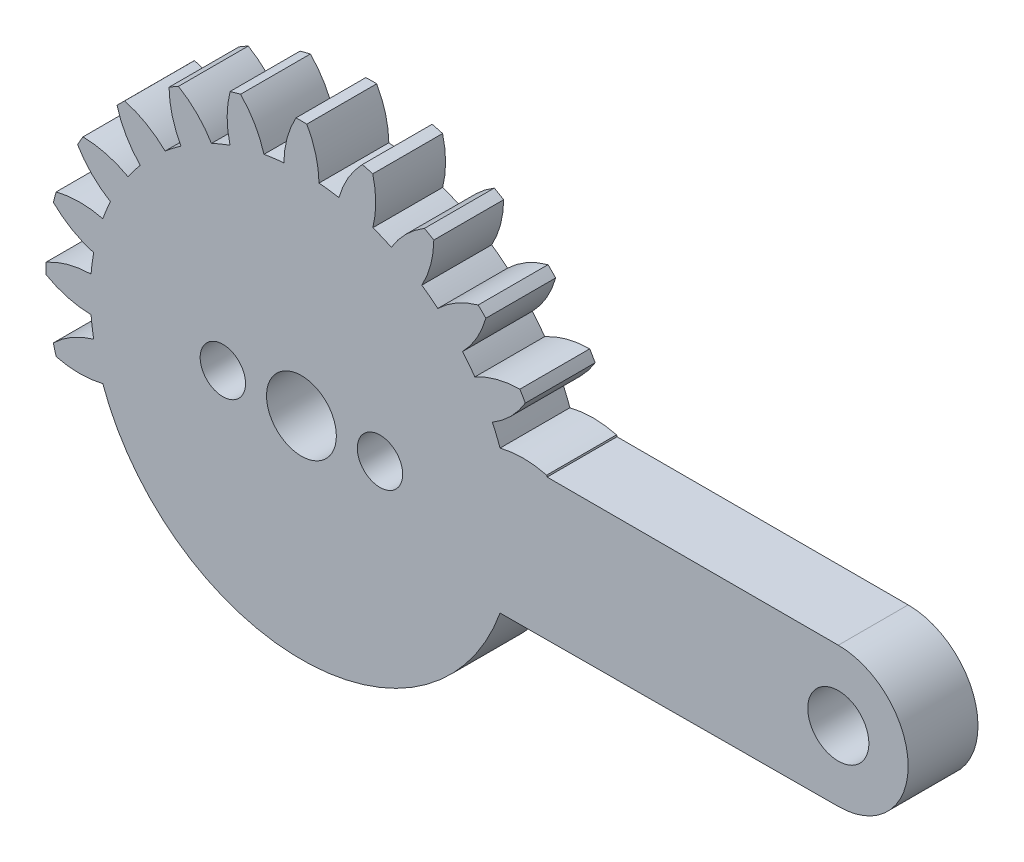
SolidWorks part; units mm, degrees
ref_plane "Front Plane" through (0, 0, 0) normal (0, 0, 1) x (1, 0, 0)
ref_plane "Top Plane" through (0, 0, 0) normal (0, 1, 0) x (1, 0, 0)
ref_plane "Right Plane" through (0, 0, 0) normal (1, 0, 0) x (0, 0, -1)
sketch "Sketch1" plane through (0, 0, 0) normal (0, 0, 1) x (1, 0, 0)
  line L0 (0, 0) -> (0, 14.63) construction
  line L1 (0, 0) -> (34.8406, 0) construction
  line L2 (11.4091, 4) -> (30.75, 4)
  line L3 (30.7686, -4) -> (11.3771, -4.0902)
  circle A0 centre (0, 0) radius 14.63
  circle A1 centre (0, 0) radius 12.09
  circle A2 centre (0, 0) radius 1.75
  arc A3 (0.31, 14.6267) -> (1.0062, 12.0481) centre (-4.3933, 11.9736) cw
  arc A4 (-0.31, 14.6267) -> (-1.0062, 12.0481) centre (4.3933, 11.9736) ccw
  arc A5 (4.0851, 14.0481) -> (4.0902, 11.3771) centre (-1.1446, 12.7027) cw
  arc A6 (3.4862, 14.2086) -> (2.1464, 11.898) centre (7.3426, 10.4285) ccw
  arc A7 (7.5818, 12.5121) -> (6.8954, 9.9308) centre (2.1821, 12.5661) cw
  arc A8 (7.0449, 12.8221) -> (5.1526, 10.937) centre (9.7915, 8.1728) ccw
  arc A9 (10.5619, 10.1234) -> (9.2308, 7.8078) centre (5.3601, 11.5731) cw
  arc A10 (10.1234, 10.5619) -> (7.8078, 9.2308) centre (11.5731, 5.3601) ccw
  arc A11 (12.8221, 7.0449) -> (10.937, 5.1526) centre (8.1728, 9.7915) cw
  arc A12 (12.5121, 7.5818) -> (9.9308, 6.8954) centre (12.5661, 2.1821) ccw
  arc A13 (14.2086, 3.4862) -> (11.898, 2.1464) centre (10.4285, 7.3426) cw
  arc A14 (14.0481, 4.0851) -> (11.3771, 4.0902) centre (12.7027, -1.1446) ccw
  arc A15 (14.6267, -0.31) -> (12.0481, -1.0062) centre (11.9736, 4.3933) cw
  arc A16 (14.6267, 0.31) -> (12.0481, 1.0062) centre (11.9736, -4.3933) ccw
  arc A17 (14.0481, -4.0851) -> (11.3771, -4.0902) centre (12.7027, 1.1446) cw
  arc A18 (14.2086, -3.4862) -> (11.898, -2.1464) centre (10.4285, -7.3426) ccw
  arc A19 (12.5121, -7.5818) -> (9.9308, -6.8954) centre (12.5661, -2.1821) cw
  arc A20 (12.8221, -7.0449) -> (10.937, -5.1526) centre (8.1728, -9.7915) ccw
  arc A21 (10.1234, -10.5619) -> (7.8078, -9.2308) centre (11.5731, -5.3601) cw
  arc A22 (10.5619, -10.1234) -> (9.2308, -7.8078) centre (5.3601, -11.5731) ccw
  arc A23 (7.0449, -12.8221) -> (5.1526, -10.937) centre (9.7915, -8.1728) cw
  arc A24 (7.5818, -12.5121) -> (6.8954, -9.9308) centre (2.1821, -12.5661) ccw
  arc A25 (3.4862, -14.2086) -> (2.1464, -11.898) centre (7.3426, -10.4285) cw
  arc A26 (4.0851, -14.0481) -> (4.0902, -11.3771) centre (-1.1446, -12.7027) ccw
  arc A27 (-0.31, -14.6267) -> (-1.0062, -12.0481) centre (4.3933, -11.9736) cw
  arc A28 (0.31, -14.6267) -> (1.0062, -12.0481) centre (-4.3933, -11.9736) ccw
  arc A29 (-4.0851, -14.0481) -> (-4.0902, -11.3771) centre (1.1446, -12.7027) cw
  arc A30 (-3.4862, -14.2086) -> (-2.1464, -11.898) centre (-7.3426, -10.4285) ccw
  arc A31 (-7.5818, -12.5121) -> (-6.8954, -9.9308) centre (-2.1821, -12.5661) cw
  arc A32 (-7.0449, -12.8221) -> (-5.1526, -10.937) centre (-9.7915, -8.1728) ccw
  arc A33 (-10.5619, -10.1234) -> (-9.2308, -7.8078) centre (-5.3601, -11.5731) cw
  arc A34 (-10.1234, -10.5619) -> (-7.8078, -9.2308) centre (-11.5731, -5.3601) ccw
  arc A35 (-12.8221, -7.0449) -> (-10.937, -5.1526) centre (-8.1728, -9.7915) cw
  arc A36 (-12.5121, -7.5818) -> (-9.9308, -6.8954) centre (-12.5661, -2.1821) ccw
  arc A37 (-14.2086, -3.4862) -> (-11.898, -2.1464) centre (-10.4285, -7.3426) cw
  arc A38 (-14.0481, -4.0851) -> (-11.3771, -4.0902) centre (-12.7027, 1.1446) ccw
  arc A39 (-14.6267, 0.31) -> (-12.0481, 1.0062) centre (-11.9736, -4.3933) cw
  arc A40 (-14.6267, -0.31) -> (-12.0481, -1.0062) centre (-11.9736, 4.3933) ccw
  arc A41 (-14.0481, 4.0851) -> (-11.3771, 4.0902) centre (-12.7027, -1.1446) cw
  arc A42 (-14.2086, 3.4862) -> (-11.898, 2.1464) centre (-10.4285, 7.3426) ccw
  arc A43 (-12.5121, 7.5818) -> (-9.9308, 6.8954) centre (-12.5661, 2.1821) cw
  arc A44 (-12.8221, 7.0449) -> (-10.937, 5.1526) centre (-8.1728, 9.7915) ccw
  arc A45 (-10.1234, 10.5619) -> (-7.8078, 9.2308) centre (-11.5731, 5.3601) cw
  arc A46 (-10.5619, 10.1234) -> (-9.2308, 7.8078) centre (-5.3601, 11.5731) ccw
  arc A47 (-7.0449, 12.8221) -> (-5.1526, 10.937) centre (-9.7915, 8.1728) cw
  arc A48 (-7.5818, 12.5121) -> (-6.8954, 9.9308) centre (-2.1821, 12.5661) ccw
  arc A49 (-3.4862, 14.2086) -> (-2.1464, 11.898) centre (-7.3426, 10.4285) cw
  arc A50 (-4.0851, 14.0481) -> (-4.0902, 11.3771) centre (1.1446, 12.7027) ccw
  arc A51 (30.75, 4) -> (30.7686, -4) centre (30.75, 0) cw
  circle A52 centre (30.75, 0) radius 1.75
  point P152 (0, 0)
  dimension "D1" = 3.5
  dimension "D2" = 24.18
  dimension "D3" = 29.26
  dimension "D6" = 5.4
  dimension "D9" = 4
  dimension "D10" = 3.5
  dimension "D4" = 0.62
  dimension "D8" = 30.75
  dimension "D11" = 1.15
  dimension "D7" = 24
extrude "Boss-Extrude2" add sketch "Sketch1" along normal blind 4 contours A51 L2 A0 L3 A52 | A0 A42 A1 A41 | A0 A44 A1 A43 | A0 A46 A1 A45 | A0 A48 A1 A47 | A0 A50 A1 A49 | A0 A4 A1 A3 | A0 A6 A1 A5 | A0 A8 A1 A7 | A0 A10 A1 A9 | A0 A12 A1 A11 | A13 A0 L2 A1 | A0 A16 A1 A15 | A0 A18 A1 L3 | A0 A14 A1 L2 | A16 A0 A13 A1 | A18 A0 A15 A1 | A0 A40 A1 A39 | A0 A38 A1 A37 | A2
sketch "Sketch2" plane through (0, 0, 4) normal (0, 0, 1) x (1, 0, 0)
  line L0 (-4.5, 0) -> (4.5, 0) construction
  circle A0 centre (4.5, 0) radius 1.3
  circle A1 centre (-4.5, 0) radius 1.3
  circle A2 centre (0, 0) radius 2
  point P4 (0, 0)
  dimension "D2" = 9
  dimension "D3" = 2.6
  dimension "D4" = 4
  dimension "D1" = 4.5
extrude "Cut-Extrude1" cut sketch "Sketch2" against normal through all
scale "Scale1" scale about centroid uniform scaling no x scale factor 1.5 y scale factor 1.5 z scale factor 1.5
